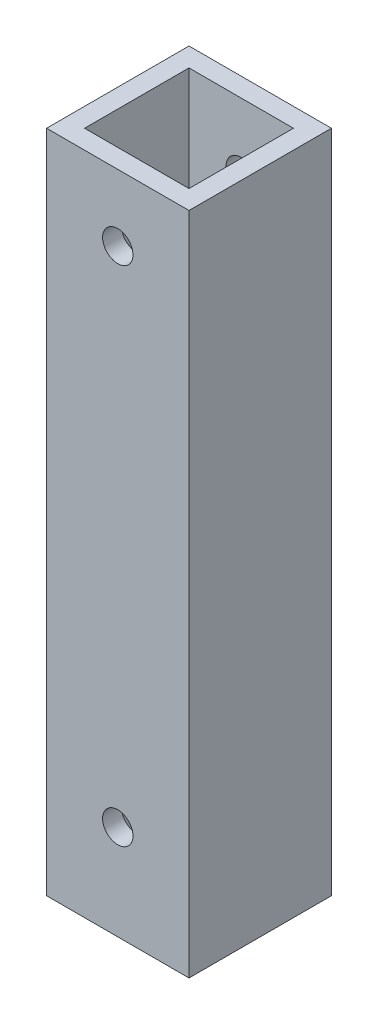
SolidWorks part; units mm, degrees
ref_plane "Front Plane" through (0, 0, 0) normal (0, 0, 1) x (1, 0, 0)
ref_plane "Top Plane" through (0, 0, 0) normal (0, 1, 0) x (1, 0, 0)
ref_plane "Right Plane" through (0, 0, 0) normal (1, 0, 0) x (0, 0, -1)
sketch "Sketch1" plane through (0, 0, 0) normal (0, 1, 0) x (1, 0, 0)
  line L0 (13, 2) -> (13, 13)
  line L1 (0, 0) -> (15, 0)
  line L2 (0, 0) -> (0, 15)
  line L3 (0, 15) -> (15, 15)
  line L4 (15, 0) -> (15, 15)
  line L5 (2, 13) -> (13, 13)
  line L6 (2, 2) -> (2, 13)
  line L7 (2, 2) -> (13, 2)
  dimension "D1" = 15
  dimension "D2" = 2
extrude "Boss-Extrude1" add sketch "Sketch1" along normal blind 70
sketch "Sketch2" plane through (0, 0, -15) normal (0, 0, -1) x (-1, 0, 0)
  circle A0 centre (-7.5, 63) radius 1.6
  circle A1 centre (-7.5, 10) radius 1.6
  dimension "D1" = 3.2
extrude "Cut-Extrude1" cut sketch "Sketch2" against normal through all
